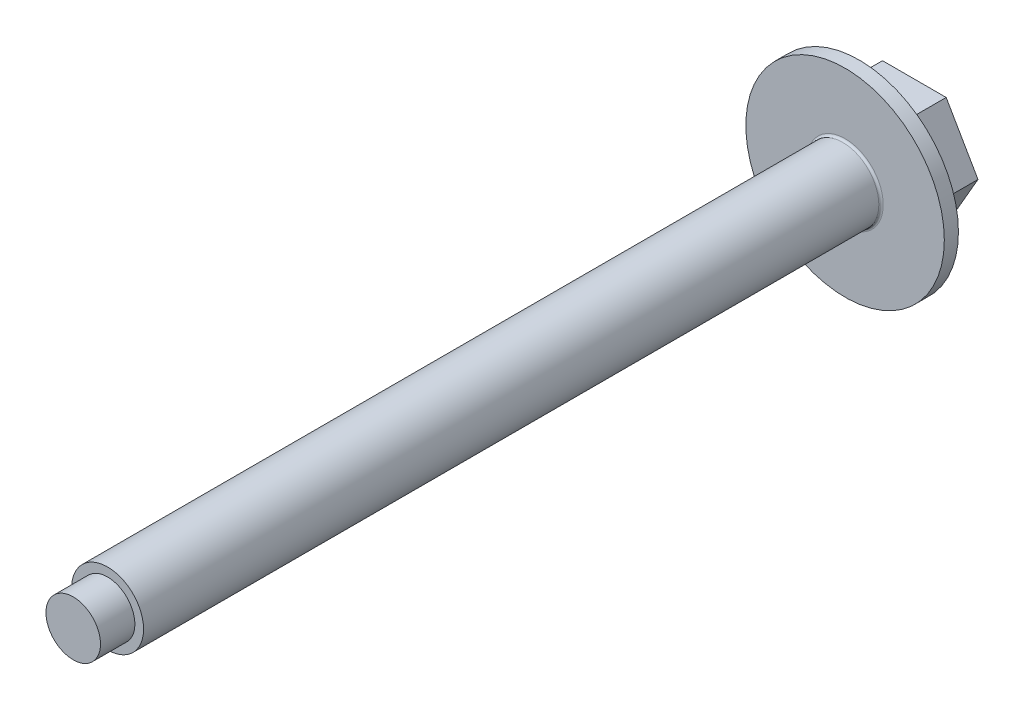
SolidWorks part; units mm, degrees
material "Ti-6Al-4VSolution treated and aged (SS)"
ref_plane "Front Plane" through (0, 0, 0) normal (0, 0, 1) x (1, 0, 0)
ref_plane "Top Plane" through (0, 0, 0) normal (0, 1, 0) x (1, 0, 0)
ref_plane "Right Plane" through (0, 0, 0) normal (1, 0, 0) x (0, 0, -1)
sketch "Sketch1" plane through (0, 0, 0) normal (0, 0, 1) x (1, 0, 0)
  line L1 (3.6662, 0) -> (1.8331, 3.175)
  line L2 (1.8331, 3.175) -> (-1.8331, 3.175)
  line L3 (-1.8331, 3.175) -> (-3.6662, 0)
  line L4 (-3.6662, 0) -> (-1.8331, -3.175)
  line L5 (-1.8331, -3.175) -> (1.8331, -3.175)
  line L6 (1.8331, -3.175) -> (3.6662, 0)
  circle A0 centre (0, 0) radius 3.175 construction
  dimension "D1" = 6.35
extrude "Boss-Extrude1" add sketch "Sketch1" along normal blind 3.175
sketch "Sketch2" plane through (0, 0, 3.175) normal (0, 0, 1) x (1, 0, 0)
  circle A0 centre (0, 0) radius 5.715
  dimension "D1" = 11.43
extrude "Boss-Extrude2" add sketch "Sketch2" along normal blind 0.8128
sketch "Sketch3" plane through (0, 0, 3.9878) normal (0, 0, 1) x (1, 0, 0)
  circle A0 centre (0, 0) radius 2.0701
  dimension "D1" = 4.1402
extrude "Boss-Extrude3" add sketch "Sketch3" along normal blind 44.45
fillet "Fillet1" radius 0.127 1 edges at (2.0701, 0, 3.9878)
sketch "Sketch4" plane through (0, 0, 48.4378) normal (0, 0, 1) x (1, 0, 0)
  circle A0 centre (0, 0) radius 1.5701
  dimension "D1" = 3.1402
extrude "Cut-Extrude1" cut sketch "Sketch4" against normal blind 1.9812 flip side to cut
equation "\"ShankLength\"= 1.75in'Max of 1.75 in, can be sized down"
equation "\"ThreadLength\"= .078in'Min of 0.078 in, can be sized up"
equation "\"D1@Cut-Extrude1\"=\"ThreadLength\""
